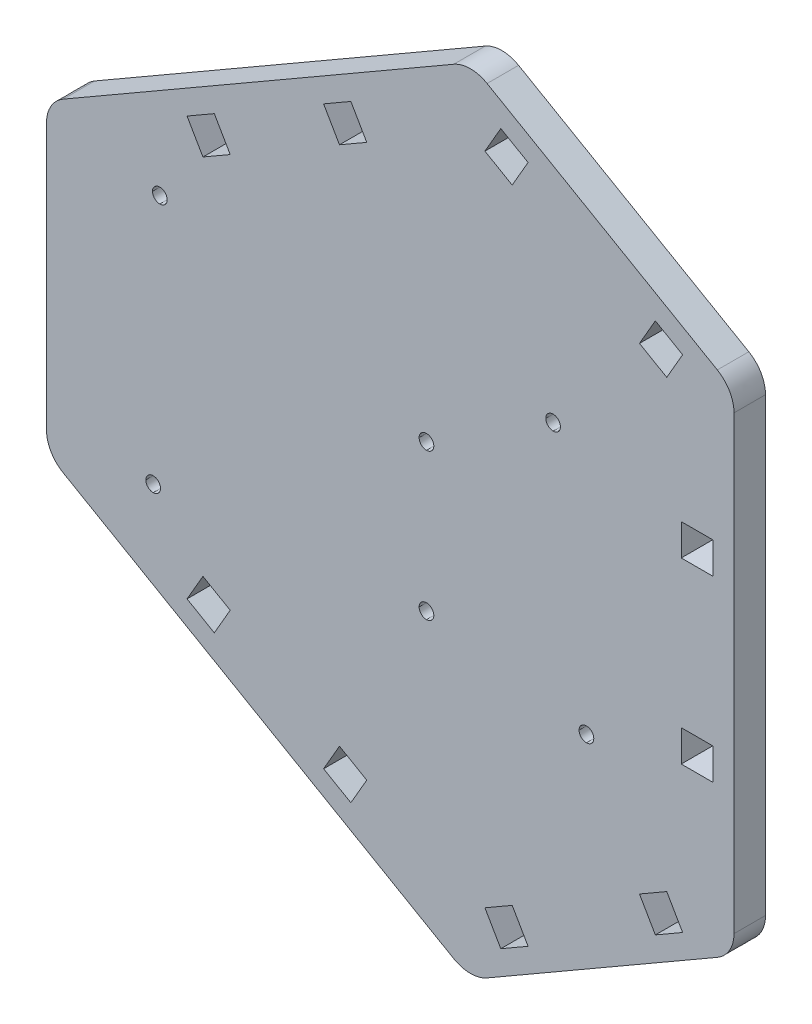
SolidWorks part; units mm, degrees
ref_plane "Alzado" through (0, 0, 0) normal (0, 0, 1) x (1, 0, 0)
ref_plane "Planta" through (0, 0, 0) normal (0, 1, 0) x (1, 0, 0)
ref_plane "Vista lateral" through (0, 0, 0) normal (1, 0, 0) x (0, 0, -1)
sketch "Corte" plane through (0, 0, 0) normal (0, 0, 1) x (1, 0, 0)
  line L0 (113.3571, 26.2106) -> (157.225, 51.5377)
  line L1 (157.225, 51.5377) -> (113.3571, 26.2106)
  line L2 (160.4, 57.037) -> (160.4, 142.9631)
  line L3 (160.4, 142.9631) -> (160.4, 57.037)
  line L4 (157.225, 148.4626) -> (113.3571, 173.7896)
  line L5 (113.3571, 173.7896) -> (157.225, 148.4626)
  line L6 (107.0071, 173.7896) -> (32.5928, 130.8265)
  line L7 (32.5928, 130.8265) -> (107.0071, 173.7896)
  line L8 (29.4178, 125.3271) -> (29.4178, 74.6728)
  line L9 (29.4178, 74.6728) -> (29.4178, 125.3271)
  line L10 (32.5928, 69.1737) -> (107.0071, 26.2106)
  line L11 (107.0071, 26.2106) -> (32.5928, 69.1737)
  line L12 (82.2097, 45.1463) -> (87.4058, 42.1462)
  line L13 (59.2191, 65.4057) -> (64.4153, 62.4057)
  line L14 (87.4058, 42.1462) -> (90.4309, 47.3856)
  line L15 (59.2191, 65.4057) -> (56.1941, 60.1662)
  line L16 (82.2097, 45.1463) -> (85.2347, 50.3857)
  line L17 (64.4153, 62.4057) -> (61.3902, 57.1662)
  line L18 (56.1941, 60.1662) -> (61.3902, 57.1662)
  line L19 (85.2347, 50.3857) -> (90.4309, 47.3856)
  line L20 (115.9705, 32.3382) -> (121.1667, 35.3382)
  line L21 (112.9455, 37.5777) -> (118.1417, 40.5777)
  line L22 (147.5866, 57.5777) -> (150.6116, 52.3382)
  line L23 (112.9455, 37.5777) -> (115.9705, 32.3382)
  line L24 (118.1417, 40.5777) -> (121.1667, 35.3382)
  line L25 (142.3904, 54.5777) -> (145.4154, 49.3382)
  line L26 (142.3904, 54.5777) -> (147.5866, 57.5777)
  line L27 (145.4154, 49.3382) -> (150.6116, 52.3382)
  line L28 (59.219, 134.5942) -> (64.4152, 137.5943)
  line L29 (64.4152, 137.5943) -> (61.3901, 142.8337)
  line L30 (59.219, 134.5942) -> (56.194, 139.8337)
  line L31 (56.194, 139.8337) -> (61.3901, 142.8337)
  line L32 (82.2095, 154.8537) -> (87.4057, 157.8537)
  line L33 (87.4057, 157.8537) -> (90.4307, 152.6143)
  line L34 (82.2095, 154.8537) -> (85.2346, 149.6143)
  line L35 (85.2346, 149.6143) -> (90.4307, 152.6143)
  line L36 (112.9454, 162.4223) -> (115.9704, 167.6618)
  line L37 (118.1416, 159.4224) -> (121.1665, 164.6618)
  line L38 (112.9454, 162.4223) -> (118.1416, 159.4224)
  line L39 (115.9704, 167.6618) -> (121.1665, 164.6618)
  line L40 (147.5865, 142.4224) -> (150.6115, 147.6619)
  line L41 (142.3903, 145.4224) -> (145.4153, 150.6619)
  line L42 (145.4153, 150.6619) -> (150.6115, 147.6619)
  line L43 (142.3903, 145.4224) -> (147.5865, 142.4224)
  line L44 (156.4, 80.0001) -> (156.4, 86.0001)
  line L45 (150.35, 120.0001) -> (156.4, 120.0001)
  line L46 (150.35, 80.0001) -> (156.4, 80.0001)
  line L47 (150.35, 86.0001) -> (156.4, 86.0001)
  line L48 (150.35, 114.0001) -> (156.4, 114.0001)
  line L49 (150.35, 80.0001) -> (150.35, 86.0001)
  line L50 (156.4, 114.0001) -> (156.4, 120.0001)
  line L51 (150.35, 114.0001) -> (150.35, 120.0001)
  line L52 (29.4178, 73.3299) -> (29.5613, 73.3299)
  line L53 (29.4178, 126.6699) -> (29.561, 126.6699)
  spline S0 degree 3 poles (157.225, 51.5377) (159.1903, 52.6729) (160.4004, 54.7675) (160.4, 57.037) knots 0 0 0 0 1 1 1 1
  spline S1 degree 3 poles (160.4, 142.9631) (160.3996, 145.2326) (159.1907, 147.3284) (157.225, 148.4626) knots 0 0 0 0 1 1 1 1
  spline S2 degree 3 poles (113.3571, 173.7896) (111.3914, 174.9238) (108.9721, 174.9248) (107.0071, 173.7896) knots 0 0 0 0 1 1 1 1
  spline S3 degree 3 poles (32.5928, 130.8265) (30.6277, 129.6913) (29.4174, 127.5965) (29.4178, 125.3271) knots 0 0 0 0 1 1 1 1
  spline S4 degree 3 poles (29.4178, 74.6728) (29.4182, 72.4034) (30.6272, 70.3079) (32.5928, 69.1737) knots 0 0 0 0 1 1 1 1
  spline S5 degree 3 poles (107.0071, 26.2106) (108.9728, 25.0763) (111.3918, 25.0753) (113.3571, 26.2106) knots 0 0 0 0 1 1 1 1
  spline S6 degree 3 poles (51.1348, 75.8699) (51.1348, 75.0984) (50.5093, 74.4729) (49.7378, 74.4729) knots 0 0 0 0 1 1 1 1
  spline S7 degree 3 poles (49.7378, 74.4729) (48.9663, 74.4729) (48.3408, 75.0984) (48.3408, 75.8699) knots 0 0 0 0 1 1 1 1
  spline S8 degree 3 poles (48.3408, 75.8699) (48.3408, 76.6415) (48.9663, 77.2669) (49.7378, 77.2669) knots 0 0 0 0 1 1 1 1
  spline S9 degree 3 poles (49.7378, 77.2669) (50.5093, 77.2669) (51.1348, 76.6415) (51.1348, 75.8699) knots 0 0 0 0 1 1 1 1
  spline S10 degree 3 poles (52.4044, 124.1299) (52.4044, 123.3584) (51.779, 122.7329) (51.0078, 122.7329) knots 0 0 0 0 1 1 1 1
  spline S11 degree 3 poles (51.0078, 122.7329) (50.2359, 122.7329) (49.6104, 123.3584) (49.6104, 124.1299) knots 0 0 0 0 1 1 1 1
  spline S12 degree 3 poles (49.6104, 124.1299) (49.6104, 124.9014) (50.2359, 125.5269) (51.0078, 125.5269) knots 0 0 0 0 1 1 1 1
  spline S13 degree 3 poles (51.0078, 125.5269) (51.779, 125.5269) (52.4044, 124.9015) (52.4044, 124.1299) knots 0 0 0 0 1 1 1 1
  spline S14 degree 3 poles (103.2048, 108.8899) (103.2048, 108.1184) (102.5793, 107.4929) (101.8078, 107.4929) knots 0 0 0 0 1 1 1 1
  spline S15 degree 3 poles (101.8078, 107.4929) (101.0363, 107.4929) (100.4108, 108.1184) (100.4108, 108.8899) knots 0 0 0 0 1 1 1 1
  spline S16 degree 3 poles (100.4108, 108.8899) (100.4108, 109.6614) (101.0363, 110.2869) (101.8078, 110.2869) knots 0 0 0 0 1 1 1 1
  spline S17 degree 3 poles (101.8078, 110.2869) (102.5793, 110.2869) (103.2048, 109.6615) (103.2048, 108.8899) knots 0 0 0 0 1 1 1 1
  spline S18 degree 3 poles (103.2048, 80.9499) (103.2048, 80.1784) (102.5793, 79.5529) (101.8078, 79.5529) knots 0 0 0 0 1 1 1 1
  spline S19 degree 3 poles (101.8078, 79.5529) (101.0363, 79.5529) (100.4108, 80.1784) (100.4108, 80.9499) knots 0 0 0 0 1 1 1 1
  spline S20 degree 3 poles (100.4108, 80.9499) (100.4108, 81.7214) (101.0363, 82.3469) (101.8078, 82.3469) knots 0 0 0 0 1 1 1 1
  spline S21 degree 3 poles (101.8078, 82.3469) (102.5793, 82.3469) (103.2048, 81.7215) (103.2048, 80.9499) knots 0 0 0 0 1 1 1 1
  spline S22 degree 3 poles (133.6848, 75.8699) (133.6848, 75.0984) (133.0593, 74.4729) (132.2878, 74.4729) knots 0 0 0 0 1 1 1 1
  spline S23 degree 3 poles (132.2878, 74.4729) (131.5163, 74.4729) (130.8908, 75.0984) (130.8908, 75.8699) knots 0 0 0 0 1 1 1 1
  spline S24 degree 3 poles (130.8908, 75.8699) (130.8908, 76.6414) (131.5163, 77.2669) (132.2878, 77.2669) knots 0 0 0 0 1 1 1 1
  spline S25 degree 3 poles (132.2878, 77.2669) (133.0593, 77.2669) (133.6848, 76.6415) (133.6848, 75.8699) knots 0 0 0 0 1 1 1 1
  spline S26 degree 3 poles (127.3348, 124.1299) (127.3348, 123.3584) (126.7093, 122.7329) (125.9378, 122.7329) knots 0 0 0 0 1 1 1 1
  spline S27 degree 3 poles (125.9378, 122.7329) (125.1663, 122.7329) (124.5408, 123.3584) (124.5408, 124.1299) knots 0 0 0 0 1 1 1 1
  spline S28 degree 3 poles (124.5408, 124.1299) (124.5408, 124.9014) (125.1663, 125.5269) (125.9378, 125.5269) knots 0 0 0 0 1 1 1 1
  spline S29 degree 3 poles (125.9378, 125.5269) (126.7093, 125.5269) (127.3348, 124.9015) (127.3348, 124.1299) knots 0 0 0 0 1 1 1 1
sketch "Grabado" plane through (0, 0, 0) normal (0, 0, 1) x (1, 0, 0)
  line L0 (35.7678, 73.3299) -> (35.7678, 126.6699)
  line L1 (35.7678, 126.6699) -> (132.2878, 126.67)
  line L2 (35.7678, 73.3299) -> (101.8078, 73.3298)
  line L3 (35.7678, 73.3299) -> (134.8278, 73.3299)
  line L4 (137.3678, 77.1399) -> (137.3678, 111.4299)
  line L5 (134.8278, 73.3299) -> (134.8278, 74.5999)
  line L6 (134.8278, 74.5999) -> (137.3678, 77.1399)
  line L7 (132.2878, 126.67) -> (134.8278, 124.1299)
  line L8 (134.8278, 113.9699) -> (137.3678, 111.4299)
  line L9 (134.8278, 113.9699) -> (134.8278, 124.1299)
  line L10 (101.8078, 74.5998) -> (104.3478, 77.1398)
  line L11 (99.2678, 126.6699) -> (101.8078, 124.1298)
  line L12 (101.8078, 113.9698) -> (104.3478, 111.4298)
  line L13 (104.3478, 77.1398) -> (104.3478, 111.4298)
  line L14 (101.8078, 73.3298) -> (101.8078, 74.5998)
  line L15 (101.8078, 113.9698) -> (101.8078, 124.1298)
extrude "Saliente-Extruir1" add sketch "Corte" against normal blind 6 contours L10 S5 L0 S0 L2 S1 L4 S2 L6 S3 L8 S4 S24 S25 S22 S23 S16 S17 S14 S15 S8 S9 S6 S7 L48 L51 L45 L50 L36 L39 L37 L38 L35 L34 L32 L33 L21 L24 L20 L23 L18
